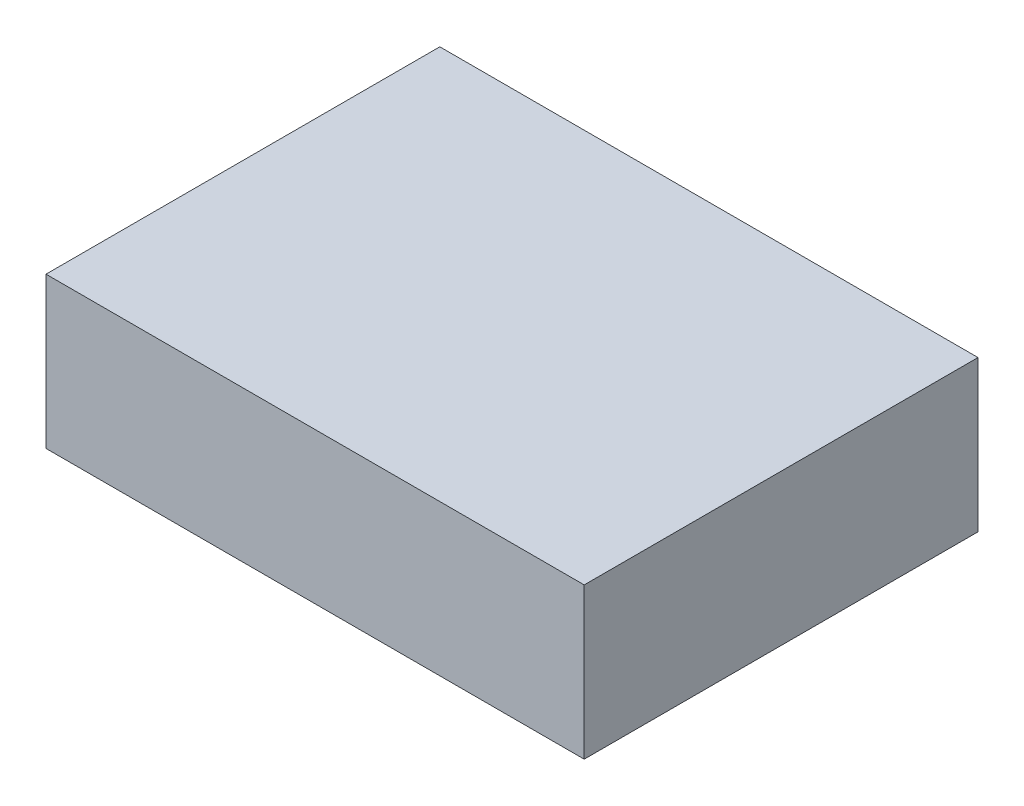
SolidWorks part; units mm, degrees
ref_plane "Front Plane" through (0, 0, 0) normal (0, 0, 1) x (1, 0, 0)
ref_plane "Top Plane" through (0, 0, 0) normal (0, 1, 0) x (1, 0, 0)
ref_plane "Right Plane" through (0, 0, 0) normal (1, 0, 0) x (0, 0, -1)
sketch "Sketch1" plane through (0, 0, 0) normal (0, 1, 0) x (1, 0, 0)
  line L1 (0, 0) -> (4.1, 0)
  line L2 (0, 0) -> (0, 3)
  line L3 (0, 3) -> (4.1, 3)
  line L4 (4.1, 0) -> (4.1, 3)
extrude "Boss-Extrude1" add sketch "Sketch1" along normal blind 1.15
ref_plane "Plane1" through (0, 0.74, 0) normal (0, 1, 0) x (1, 0, 0)
sketch "Sketch2" plane through (0, 0.74, 0) normal (0, 1, 0) x (1, 0, 0)
  line L0 (4.1, 3) -> (0, 3) construction
  circle A0 centre (2.05, 2.29) radius 0.15
  dimension "D1" = 0.71
extrude "Boss-Extrude2" add sketch "Sketch2" against normal blind 0.1 separate body
